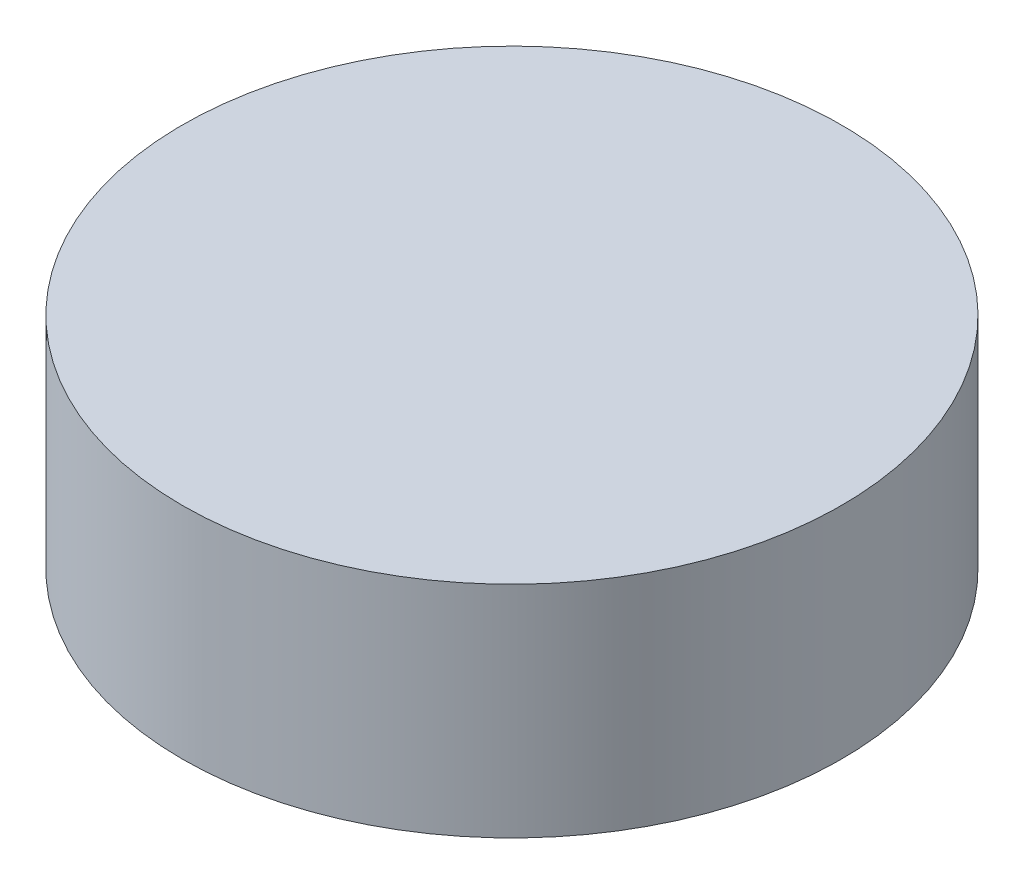
SolidWorks part; units mm, degrees
other "Markup1"
sketch "Sketch2" plane through (-150, 100, 150) normal (-0.3825, 0.8703, 0.3103) x (0.9151, 0.4033, -0.003)
ref_plane "Front Plane" through (0, 0, 0) normal (0, 0, 1) x (1, 0, 0)
ref_plane "Top Plane" through (0, 0, 0) normal (0, 1, 0) x (1, 0, 0)
ref_plane "Right Plane" through (0, 0, 0) normal (1, 0, 0) x (0, 0, -1)
sketch "Sketch1" plane through (0, 0, 0) normal (0, 1, 0) x (1, 0, 0)
  circle A0 centre (0, 0) radius 150
  dimension "D1" = 300
extrude "Boss-Extrude1" add sketch "Sketch1" along normal blind 100
